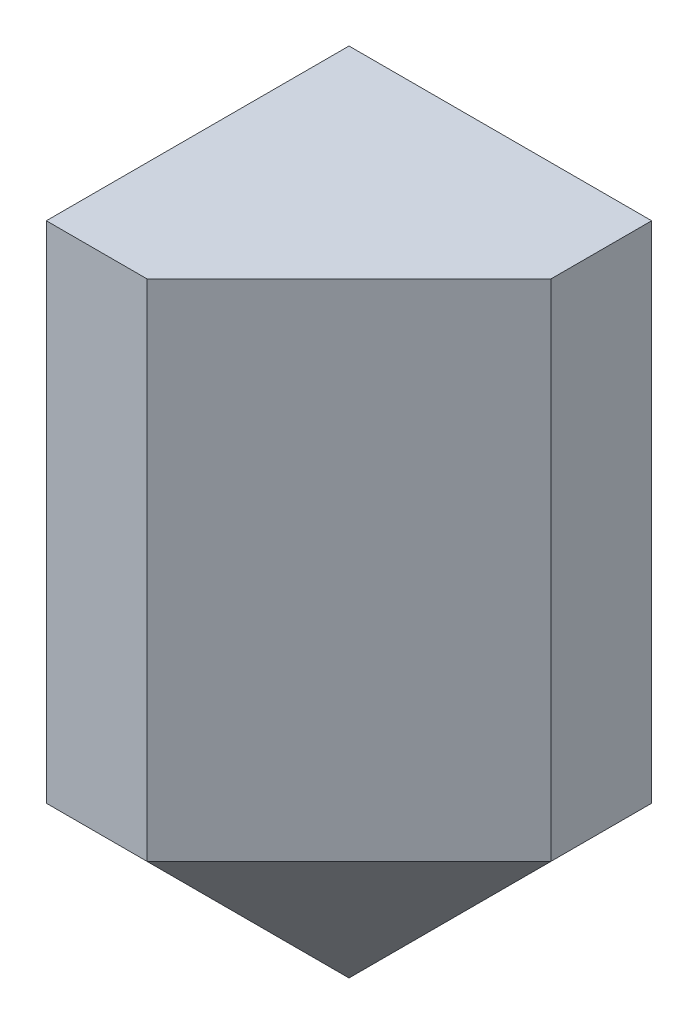
SolidWorks part; units mm, degrees
material "ABS generico"
ref_plane "Piano frontale" through (0, 0, 0) normal (0, 0, 1) x (1, 0, 0)
ref_plane "Piano superiore" through (0, 0, 0) normal (0, 1, 0) x (1, 0, 0)
ref_plane "Piano destro" through (0, 0, 0) normal (1, 0, 0) x (0, 0, -1)
sketch "Schizzo1" plane through (0, 0, 0) normal (0, 0, 1) x (1, 0, 0)
  line L1 (0, 0) -> (30, 0)
  line L2 (0, 0) -> (0, 40)
  line L3 (0, 40) -> (30, 40)
  line L4 (30, 0) -> (30, 40)
  dimension "D1" = 30
  dimension "D2" = 40
extrude "Estrusione-Estrusione1" add sketch "Schizzo1" along normal blind 30
chamfer "Smusso1" distance 20 angle 45 3 edges at (30, 20, 30) (30, 0, 15) (15, 0, 30)
sketch "Schizzo2" plane through (0, 40, 0) normal (0, 1, 0) x (1, 0, 0)
  line L0 (0, 0) -> (30, 0)
  line L1 (30, 0) -> (30, -10)
  line L2 (30, -10) -> (10, -30)
  line L3 (10, -30) -> (0, -30)
  line L4 (0, -30) -> (0, 0)
extrude "Estrusione-Estrusione2" add sketch "Schizzo2" along normal blind 30
hole_wizard "Foro per Vite M5-1" positions "Schizzo3" profile "Schizzo4" hole size "M5" standard "ISO"
sketch "Schizzo3" plane through (0, 0, 0) normal (-1, 0, 0) x (0, 0, 1)
  line L4 (0, 70) -> (30, 70) construction
  line L5 (0, 70) -> (0, 0) construction
  point P0 (18, 20)
  point P39 (0, 0)
  dimension "D1" = 18
  dimension "D2" = 50
sketch "Schizzo4" plane through (0, 20, 18) normal (0, 1, 0) x (0, 0, 1)
  line L0 (0, 0) -> (0, 16.6524)
  line L1 (0, 16.6524) -> (2.75, 15)
  line L2 (2.75, 15) -> (2.75, 0)
  line L5 (2.75, 0) -> (0, 0)
  line L10 (0, 16.6524) -> (-2.75, 15) construction
  line L11 (0, -6.35) -> (0, 107.95) construction
  dimension "Hole Dia." = 5.5
  dimension "Hole Depth" = 15
  dimension "Drill Angle" = 118
hole_wizard "Foro per Vite M5-2" positions "Schizzo3D1" profile "Schizzo5" hole size "M5" standard "ISO"
sketch3d "Schizzo3D1"
  line L0 (18, 20, 0) -> (18, 34, 0) construction
  line L2 (0, 70, 0) -> (0, 0, 0) construction
  line L4 (18, 48, 0) -> (18, 34, 0) construction
  line L5 (30, 70, 0) -> (0, 70, 0) construction
  point P2 (18, 20, 0)
  point P21 (18, 48, 0)
  point P28 (0, 0, 0)
  dimension "D1" = 18
  dimension "D2" = 14
  dimension "D3" = 22
  dimension "D4" = 14
sketch "Schizzo5" plane through (18, 20, 0) normal (1, 0, 0) x (0, 1, 0)
  line L0 (0, 0) -> (0, 16.6524)
  line L1 (0, 16.6524) -> (2.75, 15)
  line L2 (2.75, 15) -> (2.75, 0)
  line L5 (2.75, 0) -> (0, 0)
  line L10 (0, 16.6524) -> (-2.75, 15) construction
  line L11 (0, -6.35) -> (0, 107.95) construction
  dimension "Hole Dia." = 5.5
  dimension "Hole Depth" = 15
  dimension "Drill Angle" = 118
sketch "Schizzo6" plane through (0, 0, 0) normal (-1, 0, 0) x (0, 0, 1)
  line L0 (0, 70) -> (30, 70) construction
  line L1 (30, 70) -> (30, 20) construction
  circle A0 centre (15, 55) radius 10
  dimension "D1" = 20
  dimension "D2" = 15
  dimension "D3" = 15
extrude "Taglio-Estrusione1" cut sketch "Schizzo6" against normal blind 2
